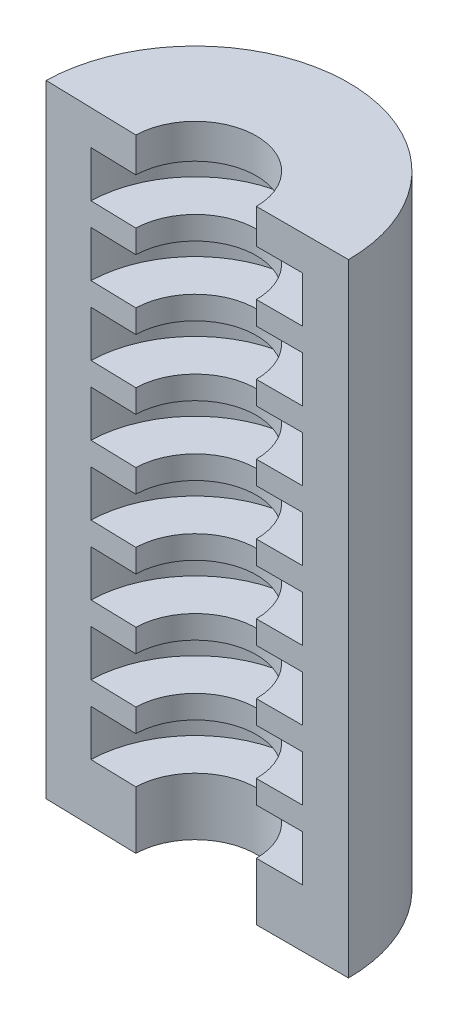
SolidWorks part; units mm, degrees
ref_plane "Front Plane" through (0, 0, 0) normal (0, 0, 1) x (1, 0, 0)
ref_plane "Top Plane" through (0, 0, 0) normal (0, 1, 0) x (1, 0, 0)
ref_plane "Right Plane" through (0, 0, 0) normal (1, 0, 0) x (0, 0, -1)
sketch "Sketch1" plane through (0, 0, 0) normal (0, 0, 1) x (1, 0, 0)
  line L0 (0, -24) -> (0, 24) construction
  line L1 (5.3, 17.2748) -> (5.3, 31.1002) construction
  line L2 (-19.4325, 21.2748) -> (4.3, 21.2748) construction
  line L3 (5.3, 21.2748) -> (23.0417, 21.2748) construction
  line L4 (5.3, 21.2748) -> (5.3, 24.2748)
  line L5 (5.3, 24.2748) -> (13.3, 24.2748)
  line L6 (13.3, 24.2748) -> (13.3, -29.7252)
  line L7 (13.3, -29.7252) -> (5.3, -29.7252)
  line L8 (5.3, -29.7252) -> (5.3, -26.7252)
  line L9 (5.3, 21.2748) -> (9.3, 21.2748)
  line L10 (9.3, 21.2748) -> (9.3, 17.2748)
  line L11 (9.3, 17.2748) -> (5.3, 17.2748)
  line L12 (5.3, 17.2748) -> (5.3, 15.2748)
  line L16 (5.3, 15.2748) -> (9.3, 15.2748)
  line L17 (9.3, 15.2748) -> (9.3, 11.2748)
  line L18 (9.3, 11.2748) -> (5.3, 11.2748)
  line L19 (5.3, 11.2748) -> (5.3, 9.2748)
  line L25 (5.3, 9.2748) -> (9.3, 9.2748)
  line L26 (9.3, 9.2748) -> (9.3, 5.2748)
  line L27 (9.3, 5.2748) -> (5.3, 5.2748)
  line L28 (5.3, 5.2748) -> (5.3, 3.2748)
  line L34 (5.3, 3.2748) -> (9.3, 3.2748)
  line L35 (9.3, 3.2748) -> (9.3, -0.7252)
  line L36 (9.3, -0.7252) -> (5.3, -0.7252)
  line L37 (5.3, -0.7252) -> (5.3, -2.7252)
  line L43 (5.3, -2.7252) -> (9.3, -2.7252)
  line L44 (9.3, -2.7252) -> (9.3, -6.7252)
  line L45 (9.3, -6.7252) -> (5.3, -6.7252)
  line L46 (5.3, -6.7252) -> (5.3, -8.7252)
  line L52 (5.3, -8.7252) -> (9.3, -8.7252)
  line L53 (9.3, -8.7252) -> (9.3, -12.7252)
  line L54 (9.3, -12.7252) -> (5.3, -12.7252)
  line L55 (5.3, -12.7252) -> (5.3, -14.7252)
  line L61 (5.3, -14.7252) -> (9.3, -14.7252)
  line L62 (9.3, -14.7252) -> (9.3, -18.7252)
  line L63 (9.3, -18.7252) -> (5.3, -18.7252)
  line L64 (5.3, -18.7252) -> (5.3, -20.7252)
  line L70 (5.3, -20.7252) -> (9.3, -20.7252)
  line L71 (9.3, -20.7252) -> (9.3, -24.7252)
  line L72 (9.3, -24.7252) -> (5.3, -24.7252)
  line L73 (5.3, -24.7252) -> (5.3, -26.7252)
  point P4 (0, 0)
  dimension "D1" = 48
  dimension "D2" = 5.3
  dimension "D3" = 8
  dimension "D4" = 54
  dimension "D8" = 4
  dimension "D9" = 5
  dimension "D10" = 2
  dimension "D12" = 8
revolve "Revolve1" add sketch "Sketch1" angle 178.5 about L0
ref_plane "Plane1" through (0, 0, -5) normal (0, 0, 1) x (1, 0, 0)
sketch "Sketch2" plane through (0, 0, -5) normal (0, 0, 1) x (1, 0, 0)
  line L0 (0, 29.2149) -> (0, 22.0331) construction
